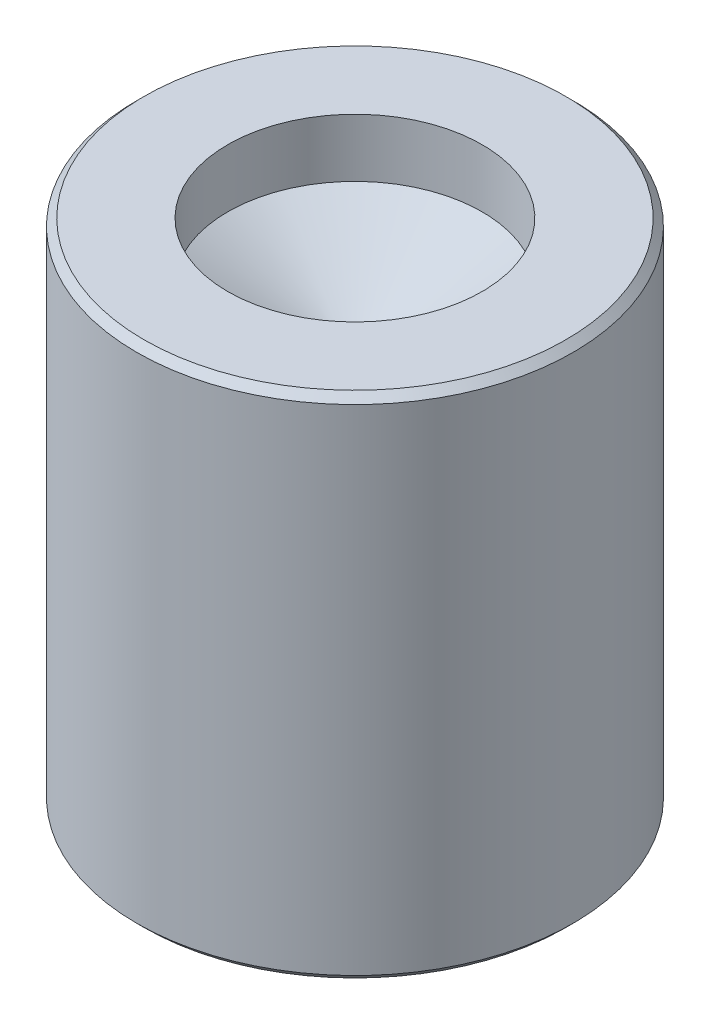
SolidWorks part; units mm, degrees
ref_plane "Plan de face" through (0, 0, 0) normal (0, 0, 1) x (1, 0, 0)
ref_plane "Plan de dessus" through (0, 0, 0) normal (0, 1, 0) x (1, 0, 0)
ref_plane "Plan de droite" through (0, 0, 0) normal (1, 0, 0) x (0, 0, -1)
sketch "Esquisse1" plane through (0, 0, 0) normal (0, 1, 0) x (1, 0, 0)
  circle A0 centre (0, 0) radius 30
  dimension "D1" = 60
extrude "Boss.-Extru.1" add sketch "Esquisse1" along normal blind 70
hole_wizard "Dégagement #82" positions "Esquisse6" profile "Esquisse5" hole size "#8" standard "Ansi Inch"
sketch "Esquisse6" plane through (0, 70, 0) normal (0, 1, 0) x (1, 0, 0)
  point P0 (0, 0)
sketch "Esquisse5" plane through (0, 70, 0) normal (1, 0, 0) x (0, 0, 1)
  line L0 (0, 0) -> (0, 18.5151)
  line L1 (0, 18.5151) -> (17.5, 8)
  line L2 (17.5, 8) -> (17.5, 0)
  line L5 (17.5, 0) -> (0, 0)
  line L10 (0, 18.5151) -> (-17.5, 8) construction
  line L11 (0, -6.35) -> (0, 107.95) construction
  dimension "Diamètre du perçage" = 35
  dimension "Profondeur du perçage" = 8
  dimension "Angle de pointe" = 118
chamfer "Chanfrein1" distance 1 angle 45 2 edges at (0, 0, 30) (0, 70, 30)
